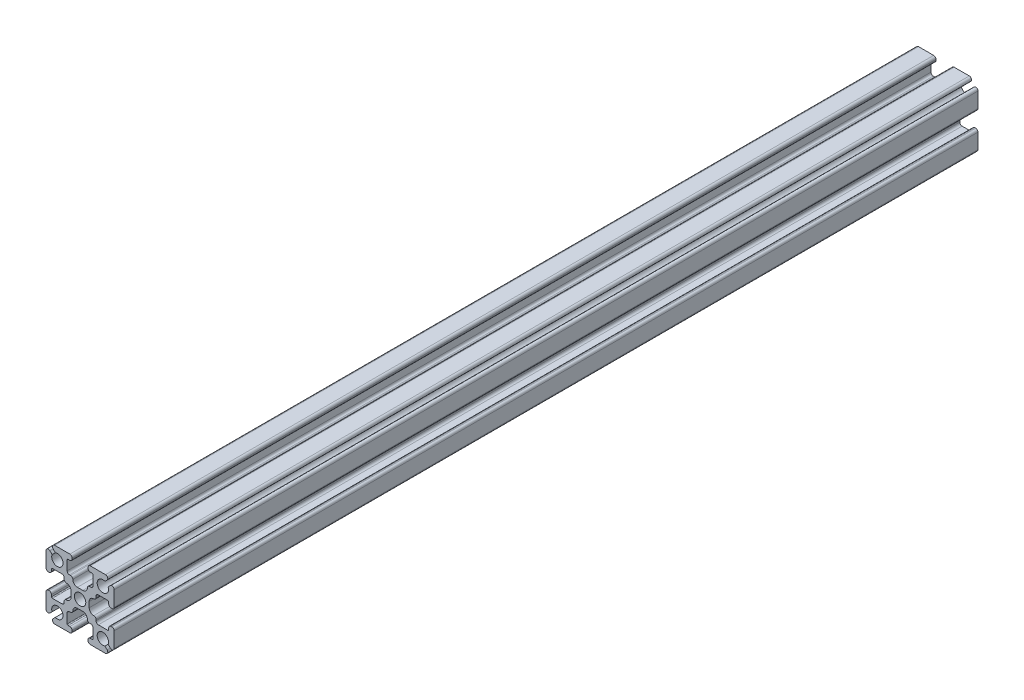
SolidWorks part; units mm, degrees
ref_plane "Front" through (0, 0, 0) normal (0, 0, 1) x (1, 0, 0)
ref_plane "Top" through (0, 0, 0) normal (0, 1, 0) x (1, 0, 0)
ref_plane "Right" through (0, 0, 0) normal (1, 0, 0) x (0, 0, -1)
sketch "Sketch1" plane through (0, 0, 0) normal (0, 0, 1) x (1, 0, 0)
  line L0 (6.6464, 5.9393) -> (6.1636, 5.4565)
  line L1 (5.4565, 6.1636) -> (5.9393, 6.6464)
  line L2 (5.5858, 7.5) -> (2.25, 7.5)
  line L3 (1.75, 7) -> (1.75, 6.8)
  line L4 (2.25, 6.3) -> (2.65, 6.3)
  line L5 (2.85, 6.1) -> (2.85, 4)
  line L6 (2.35, 3.5) -> (2.1, 3.5)
  line L7 (0.6, 2) -> (-0.6, 2)
  line L8 (-2.1, 3.5) -> (-2.35, 3.5)
  line L9 (-2.85, 4) -> (-2.85, 6.1)
  line L10 (-2.65, 6.3) -> (-2.25, 6.3)
  line L11 (-1.75, 6.8) -> (-1.75, 7)
  line L12 (-2.25, 7.5) -> (-5.5858, 7.5)
  line L13 (-5.9393, 6.6464) -> (-5.4565, 6.1636)
  line L14 (-6.1636, 5.4565) -> (-6.6464, 5.9393)
  line L15 (-7.5, 5.5858) -> (-7.5, 2.25)
  line L16 (-7, 1.75) -> (-6.8, 1.75)
  line L17 (-6.3, 2.25) -> (-6.3, 2.65)
  line L18 (-6.1, 2.85) -> (-4, 2.85)
  line L19 (-3.5, 2.35) -> (-3.5, 2.1)
  line L20 (-2, 0.6) -> (-2, -0.6)
  line L21 (-3.5, -2.1) -> (-3.5, -2.35)
  line L22 (-4, -2.85) -> (-6.1, -2.85)
  line L23 (-6.3, -2.65) -> (-6.3, -2.25)
  line L24 (-6.8, -1.75) -> (-7, -1.75)
  line L25 (-7.5, -2.25) -> (-7.5, -5.5858)
  line L26 (-6.6464, -5.9393) -> (-6.1636, -5.4565)
  line L27 (-5.4565, -6.1636) -> (-5.9393, -6.6464)
  line L28 (-5.5858, -7.5) -> (-2.25, -7.5)
  line L29 (-1.75, -7) -> (-1.75, -6.8)
  line L30 (-2.25, -6.3) -> (-2.65, -6.3)
  line L31 (-2.85, -6.1) -> (-2.85, -4)
  line L32 (-2.35, -3.5) -> (-2.1, -3.5)
  line L33 (-0.6, -2) -> (0.6, -2)
  line L34 (2.1, -3.5) -> (2.35, -3.5)
  line L35 (2.85, -4) -> (2.85, -6.1)
  line L36 (2.65, -6.3) -> (2.25, -6.3)
  line L37 (1.75, -6.8) -> (1.75, -7)
  line L38 (2.25, -7.5) -> (5.5858, -7.5)
  line L39 (5.9393, -6.6464) -> (5.4565, -6.1636)
  line L40 (6.1636, -5.4565) -> (6.6464, -5.9393)
  line L41 (7.5, -5.5858) -> (7.5, -2.25)
  line L42 (7, -1.75) -> (6.8, -1.75)
  line L43 (6.3, -2.25) -> (6.3, -2.65)
  line L44 (6.1, -2.85) -> (4, -2.85)
  line L45 (3.5, -2.35) -> (3.5, -2.1)
  line L46 (2, -0.6) -> (2, 0.6)
  line L47 (3.5, 2.1) -> (3.5, 2.35)
  line L48 (4, 2.85) -> (6.1, 2.85)
  line L49 (6.3, 2.65) -> (6.3, 2.25)
  line L50 (6.8, 1.75) -> (7, 1.75)
  line L51 (7.5, 2.25) -> (7.5, 5.5858)
  circle A0 centre (0, 0) radius 1.25
  arc A1 (6.1636, 5.4565) -> (5.4565, 6.1636) centre (5, 5) cw
  arc A2 (5.9393, 6.6464) -> (5.5858, 7.5) centre (5.5858, 7) ccw
  arc A3 (2.25, 7.5) -> (1.75, 7) centre (2.25, 7) ccw
  arc A4 (1.75, 6.8) -> (2.25, 6.3) centre (2.25, 6.8) ccw
  arc A5 (2.65, 6.3) -> (2.85, 6.1) centre (2.65, 6.1) cw
  arc A6 (2.85, 4) -> (2.35, 3.5) centre (2.35, 4) cw
  arc A7 (2.1, 3.5) -> (1.6, 3) centre (2.1, 3) ccw
  arc A8 (1.6, 3) -> (0.6, 2) centre (0.6, 3) cw
  arc A9 (-0.6, 2) -> (-1.6, 3) centre (-0.6, 3) cw
  arc A10 (-1.6, 3) -> (-2.1, 3.5) centre (-2.1, 3) ccw
  arc A11 (-2.35, 3.5) -> (-2.85, 4) centre (-2.35, 4) cw
  arc A12 (-2.85, 6.1) -> (-2.65, 6.3) centre (-2.65, 6.1) cw
  arc A13 (-2.25, 6.3) -> (-1.75, 6.8) centre (-2.25, 6.8) ccw
  arc A14 (-1.75, 7) -> (-2.25, 7.5) centre (-2.25, 7) ccw
  arc A15 (-5.5858, 7.5) -> (-5.9393, 6.6464) centre (-5.5858, 7) ccw
  arc A16 (-5.4565, 6.1636) -> (-6.1636, 5.4565) centre (-5, 5) cw
  arc A17 (-6.6464, 5.9393) -> (-7.5, 5.5858) centre (-7, 5.5858) ccw
  arc A18 (-7.5, 2.25) -> (-7, 1.75) centre (-7, 2.25) ccw
  arc A19 (-6.8, 1.75) -> (-6.3, 2.25) centre (-6.8, 2.25) ccw
  arc A20 (-6.3, 2.65) -> (-6.1, 2.85) centre (-6.1, 2.65) cw
  arc A21 (-4, 2.85) -> (-3.5, 2.35) centre (-4, 2.35) cw
  arc A22 (-3.5, 2.1) -> (-3, 1.6) centre (-3, 2.1) ccw
  arc A23 (-3, 1.6) -> (-2, 0.6) centre (-3, 0.6) cw
  arc A24 (-2, -0.6) -> (-3, -1.6) centre (-3, -0.6) cw
  arc A25 (-3, -1.6) -> (-3.5, -2.1) centre (-3, -2.1) ccw
  arc A26 (-3.5, -2.35) -> (-4, -2.85) centre (-4, -2.35) cw
  arc A27 (-6.1, -2.85) -> (-6.3, -2.65) centre (-6.1, -2.65) cw
  arc A28 (-6.3, -2.25) -> (-6.8, -1.75) centre (-6.8, -2.25) ccw
  arc A29 (-7, -1.75) -> (-7.5, -2.25) centre (-7, -2.25) ccw
  arc A30 (-7.5, -5.5858) -> (-6.6464, -5.9393) centre (-7, -5.5858) ccw
  arc A31 (-6.1636, -5.4565) -> (-5.4565, -6.1636) centre (-5, -5) cw
  arc A32 (-5.9393, -6.6464) -> (-5.5858, -7.5) centre (-5.5858, -7) ccw
  arc A33 (-2.25, -7.5) -> (-1.75, -7) centre (-2.25, -7) ccw
  arc A34 (-1.75, -6.8) -> (-2.25, -6.3) centre (-2.25, -6.8) ccw
  arc A35 (-2.65, -6.3) -> (-2.85, -6.1) centre (-2.65, -6.1) cw
  arc A36 (-2.85, -4) -> (-2.35, -3.5) centre (-2.35, -4) cw
  arc A37 (-2.1, -3.5) -> (-1.6, -3) centre (-2.1, -3) ccw
  arc A38 (-1.6, -3) -> (-0.6, -2) centre (-0.6, -3) cw
  arc A39 (0.6, -2) -> (1.6, -3) centre (0.6, -3) cw
  arc A40 (1.6, -3) -> (2.1, -3.5) centre (2.1, -3) ccw
  arc A41 (2.35, -3.5) -> (2.85, -4) centre (2.35, -4) cw
  arc A42 (2.85, -6.1) -> (2.65, -6.3) centre (2.65, -6.1) cw
  arc A43 (2.25, -6.3) -> (1.75, -6.8) centre (2.25, -6.8) ccw
  arc A44 (1.75, -7) -> (2.25, -7.5) centre (2.25, -7) ccw
  arc A45 (5.5858, -7.5) -> (5.9393, -6.6464) centre (5.5858, -7) ccw
  arc A46 (5.4565, -6.1636) -> (6.1636, -5.4565) centre (5, -5) cw
  arc A47 (6.6464, -5.9393) -> (7.5, -5.5858) centre (7, -5.5858) ccw
  arc A48 (7.5, -2.25) -> (7, -1.75) centre (7, -2.25) ccw
  arc A49 (6.8, -1.75) -> (6.3, -2.25) centre (6.8, -2.25) ccw
  arc A50 (6.3, -2.65) -> (6.1, -2.85) centre (6.1, -2.65) cw
  arc A51 (4, -2.85) -> (3.5, -2.35) centre (4, -2.35) cw
  arc A52 (3.5, -2.1) -> (3, -1.6) centre (3, -2.1) ccw
  arc A53 (3, -1.6) -> (2, -0.6) centre (3, -0.6) cw
  arc A54 (2, 0.6) -> (3, 1.6) centre (3, 0.6) cw
  arc A55 (3, 1.6) -> (3.5, 2.1) centre (3, 2.1) ccw
  arc A56 (3.5, 2.35) -> (4, 2.85) centre (4, 2.35) cw
  arc A57 (6.1, 2.85) -> (6.3, 2.65) centre (6.1, 2.65) cw
  arc A58 (6.3, 2.25) -> (6.8, 1.75) centre (6.8, 2.25) ccw
  arc A59 (7, 1.75) -> (7.5, 2.25) centre (7, 2.25) ccw
  arc A60 (7.5, 5.5858) -> (6.6464, 5.9393) centre (7, 5.5858) ccw
extrude "Boss-Extrude1" add sketch "Sketch1" along normal blind 190
